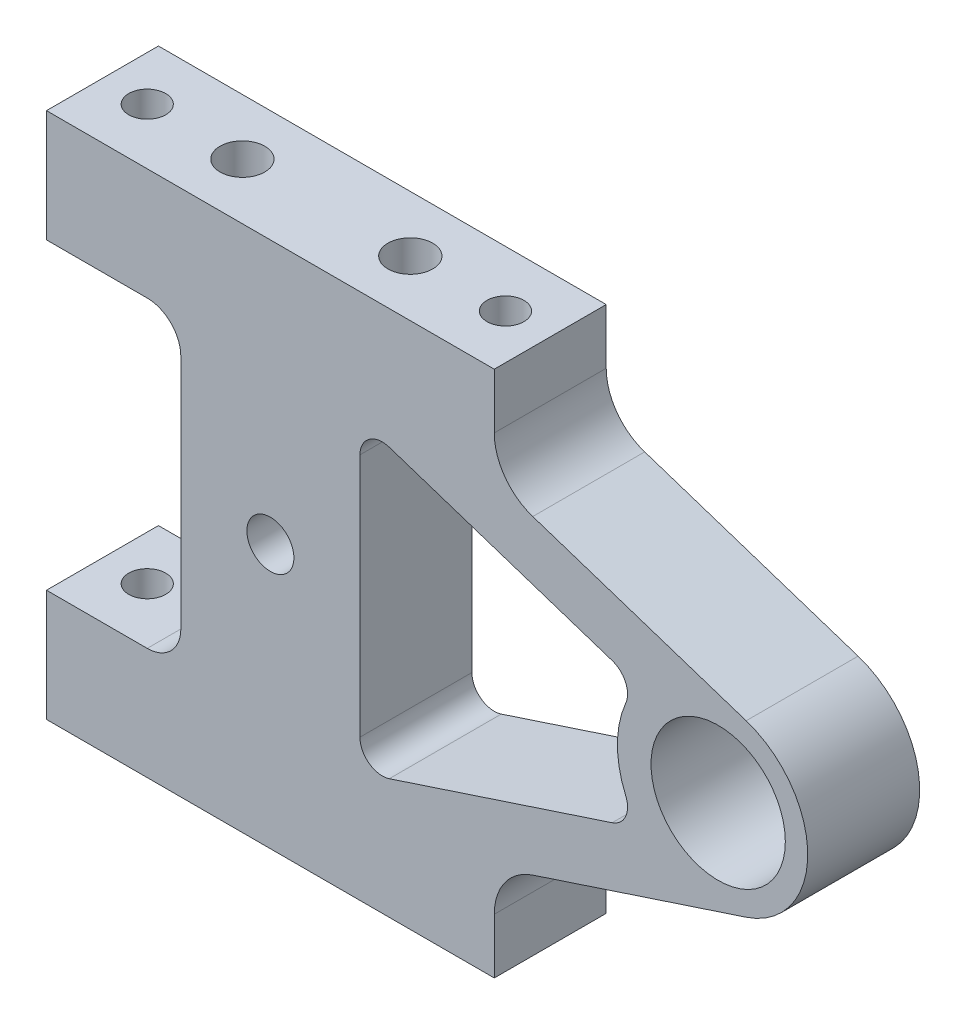
SolidWorks part; units mm, degrees
material "6061 合金"
ref_plane "前视基准面" through (0, 0, 0) normal (0, 0, 1) x (1, 0, 0)
ref_plane "上视基准面" through (0, 0, 0) normal (0, 1, 0) x (1, 0, 0)
ref_plane "右视基准面" through (0, 0, 0) normal (1, 0, 0) x (0, 0, -1)
other "Configuration Table"
sketch "草图1" plane through (0, 0, 0) normal (0, 0, 1) x (1, 0, 0)
  line L1 (-20, -23.55) -> (20, -23.55)
  line L2 (-20, -23.55) -> (-20, 23.55)
  line L3 (-20, 23.55) -> (20, 23.55)
  line L4 (20, -23.55) -> (20, 23.55)
  line L5 (-20, -23.55) -> (20, 23.55) construction
  line L6 (-20, 23.55) -> (20, -23.55) construction
  point P0 (0, 0)
  dimension "D1" = 47.1
  dimension "D2" = 40
extrude "凸台-拉伸1" add sketch "草图1" along normal mid plane 10
sketch "草图2" plane through (0, 23.55, 0) normal (0, 1, 0) x (1, 0, 0)
  line L0 (-16, 0) -> (16, 0) construction
  line L1 (20, -5) -> (20, 5) construction
  point P4 (0, 0)
  dimension "D1" = 4
hole_wizard "M4 螺纹孔1" positions "草图3" profile "草图4" tap size "M4" standard "GB"
sketch "草图3" plane through (0, 23.55, 0) normal (0, 1, 0) x (1, 0, 0)
  point P0 (-16, 0)
  point P3 (16, 0)
sketch "草图4" plane through (-16, 23.55, 0) normal (1, 0, 0) x (0, 0, 1)
  line L0 (0, 0) -> (0, 11.0914)
  line L1 (0, 11.0914) -> (1.65, 10.1)
  line L2 (1.65, 10.1) -> (1.65, 0)
  line L5 (1.65, 0) -> (0, 0)
  line L10 (0, 11.0914) -> (-1.65, 10.1) construction
  line L11 (0, -6.35) -> (0, 107.95) construction
  dimension "螺纹孔钻头直径" = 3.3
  dimension "螺纹孔钻头深度" = 10.1
  dimension "导头角度" = 118
cosmetic thread "孔螺蚊线1" parameters "D1"=8, "D2"=4
cosmetic thread "孔螺蚊线2" parameters "D1"=8, "D2"=4
mirror "镜向1" about plane through (0, 0, 0) normal (0, 1, 0) of "M4 螺纹孔1"
sketch "草图5" plane through (0, 0, 5) normal (0, 0, 1) x (1, 0, 0)
  circle A0 centre (0, 0) radius 2.1
  dimension "D1" = 4.2
extrude "M5螺纹孔" cut sketch "草图5" against normal mid plane 50
cosmetic thread "装饰螺纹线2" parameters "D1"=5, "D2"=5
sketch "草图6" plane through (0, 0, 5) normal (0, 0, 1) x (1, 0, 0)
  line L0 (0, 0) -> (40, 0) construction
  line L1 (42.4996, 7.5995) -> (20, 15)
  line L2 (20, -23.55) -> (20, 23.55) construction
  line L3 (20, 15) -> (20, -15)
  line L4 (42.4996, -7.5995) -> (20, -15)
  circle A0 centre (40, 0) radius 6
  arc A1 (42.4996, -7.5995) -> (42.4996, 7.5995) centre (40, 0) ccw
  point P12 (20, 0)
  dimension "D2" = 12
  dimension "D3" = 2
  dimension "D1" = 40
  dimension "D4" = 15
extrude "凸台" add sketch "草图6" against normal up to surface (10 mm away) up to face at (-2.1, 0, -5)
fillet "圆角1" radius 5 2 edges at (20, -15, 0) (20, 15, 0)
sketch "草图7" plane through (0, 0, 5) normal (0, 0, 1) x (1, 0, 0)
  line L0 (-20, 23.55) -> (-20, -23.55) construction
  line L1 (-32, -13.55) -> (-8, -13.55)
  line L2 (-32, -13.55) -> (-32, 13.55)
  line L3 (-32, 13.55) -> (-8, 13.55)
  line L4 (-8, -13.55) -> (-8, 13.55)
  line L5 (-32, -13.55) -> (-8, 13.55) construction
  line L6 (-32, 13.55) -> (-8, -13.55) construction
  line L7 (20, 23.55) -> (-20, 23.55) construction
  circle A0 centre (0, 0) radius 2.1 construction
  point P0 (-20, 0)
  dimension "D1" = 8
  dimension "D2" = 10
extrude "切除-拉伸1" cut sketch "草图7" against normal up to surface (10 mm away)
fillet "圆角2" radius 3 2 edges at (-8, 13.55, 0) (-8, -13.55, 0)
sketch "草图9" plane through (0, 23.55, 0) normal (0, 1, 0) x (1, 0, 0)
  line L0 (-7.5, 0) -> (7.5, 0) construction
  circle A0 centre (7.5, 0) radius 2
  circle A1 centre (-7.5, 0) radius 2
  point P4 (0, 0)
  dimension "D2" = 4
  dimension "D1" = 15
hole_wizard "Ø4.0mm 暗销孔1" positions "草图10" profile "草图11" hole size "Ø4.0" standard "GB"
sketch "草图10" plane through (0, 23.55, 0) normal (0, 1, 0) x (1, 0, 0)
  point P0 (-7.5, 0)
  point P3 (7.5, 0)
sketch "草图11" plane through (-7.5, 23.55, 0) normal (1, 0, 0) x (0, 0, 1)
  line L0 (0, 0) -> (0, 6.2017)
  line L1 (0, 6.2017) -> (2, 5)
  line L2 (2, 5) -> (2, 0)
  line L5 (2, 0) -> (0, 0)
  line L10 (0, 6.2017) -> (-2, 5) construction
  line L11 (0, -6.35) -> (0, 107.95) construction
  dimension "孔直径" = 4
  dimension "孔深度" = 5
  dimension "导头角度" = 118
mirror "镜向3" about plane through (0, 0, 0) normal (0, 1, 0) of "Ø4.0mm 暗销孔1"
sketch "草图12" plane through (0, 0, 5) normal (0, 0, 1) x (1, 0, 0)
  line L0 (8, 13.6835) -> (8, -13.6835)
  line L1 (8, -13.6835) -> (32.8769, -5.501)
  line L2 (23.4377, -13.8693) -> (42.4996, -7.5995) construction
  line L3 (8, 13.6835) -> (32.8769, 5.501)
  line L4 (42.4996, 7.5995) -> (23.4377, 13.8693) construction
  line L5 (0, 0) -> (0, -14.3482) construction
  arc A0 (32.8769, 5.501) -> (32.8769, -5.501) centre (40, 0) ccw
  dimension "D1" = 18
  dimension "D2" = 5
  dimension "D3" = 5
  dimension "D4" = 16
extrude "切除-拉伸3" cut sketch "草图12" against normal blind 10
fillet "圆角3" radius 2 4 edges at (32.8769, 5.501, 0) (32.8769, -5.501, 0) (8, -13.6835, 0) (8, 13.6835, 0)
